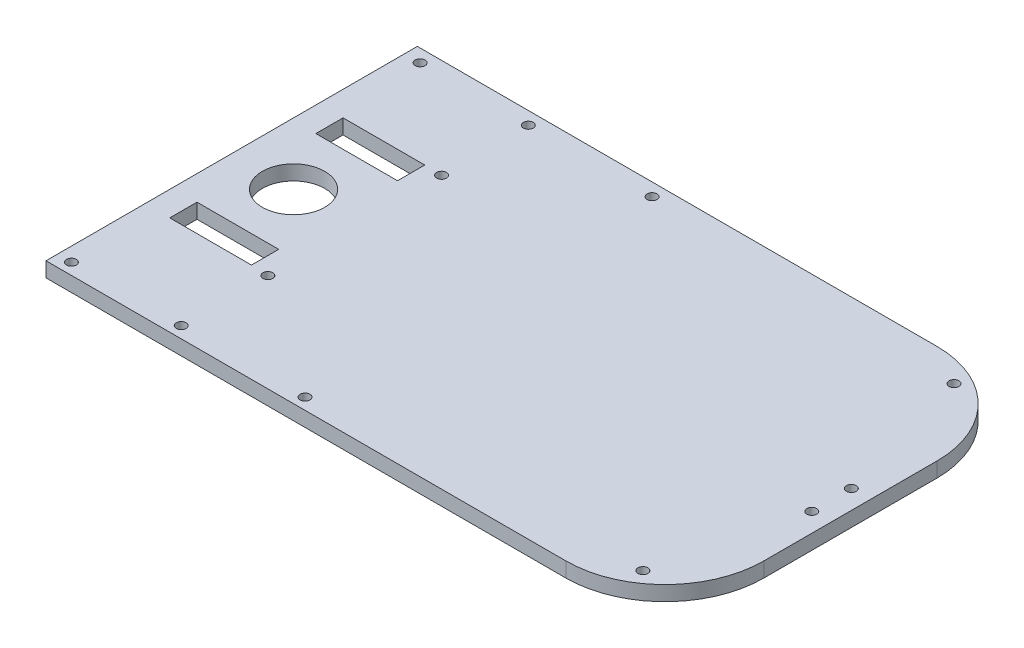
SolidWorks part; units mm, degrees
ref_plane "Front Plane" through (0, 0, 0) normal (0, 0, 1) x (1, 0, 0)
ref_plane "Top Plane" through (0, 0, 0) normal (0, 1, 0) x (1, 0, 0)
ref_plane "Right Plane" through (0, 0, 0) normal (1, 0, 0) x (0, 0, -1)
sketch "Sketch1" plane through (0, 0, 0) normal (0, 1, 0) x (1, 0, 0)
  line L1 (0, 0) -> (210, 0)
  line L2 (0, 0) -> (0, 150)
  line L3 (0, 150) -> (210, 150)
  line L4 (250, 40) -> (250, 110)
  arc A0 (250, 110) -> (210, 150) centre (210, 110) ccw
  arc A1 (210, 0) -> (250, 40) centre (210, 40) ccw
  point P7 (250, 150)
  dimension "D3" = 40
  dimension "D4" = 40
  dimension "D1" = 250
  dimension "D2" = 150
extrude "Boss-Extrude1" add sketch "Sketch1" along normal blind 6
sketch "Sketch2" plane through (0, 0, 0) normal (0, -1, 0) x (1, 0, 0)
  line L0 (0, 0) -> (210, 0) construction
  line L2 (0, -150) -> (0, 0) construction
  circle A0 centre (25, -75) radius 12.5979
  dimension "D1" = 25.1959
  dimension "D2" = 75
  dimension "D3" = 25
extrude "Cut-Extrude1" cut sketch "Sketch2" against normal through all
sketch "Sketch3" plane through (0, 6, 0) normal (0, 1, 0) x (1, 0, 0)
  line L0 (210, 150) -> (0, 150) construction
  line L1 (0, 150) -> (0, 0) construction
  circle A0 centre (6.3109, 144.8171) radius 2
  dimension "D1" = 4
  dimension "D2" = 5.1829
  dimension "D3" = 6.3109
sketch "Sketch4" plane through (0, 6, 0) normal (0, 1, 0) x (1, 0, 0)
  line L0 (0, 0) -> (210, 0) construction
  line L1 (0, 150) -> (0, 0) construction
  circle A0 centre (5.6357, 4.6328) radius 2
  dimension "D1" = 4
  dimension "D2" = 4.6328
  dimension "D3" = 5.6357
sketch "Sketch5" plane through (0, 6, 0) normal (0, 1, 0) x (1, 0, 0)
  circle A0 centre (226.3641, 140.4212) radius 2
  arc A1 (250, 110) -> (210, 150) centre (210, 110) ccw construction
  dimension "D1" = 4
  dimension "D2" = 34.5433
  dimension "D3" = 30.4212
sketch "Sketch6" plane through (0, 6, 0) normal (0, 1, 0) x (1, 0, 0)
  circle A0 centre (228.9499, 12.1646) radius 2
  arc A1 (210, 0) -> (250, 40) centre (210, 40) ccw construction
  dimension "D1" = 4
  dimension "D2" = 33.6736
  dimension "D3" = 18.9499
sketch "Sketch8" plane through (0, 6, 0) normal (0, 1, 0) x (1, 0, 0)
  line L0 (250, 40) -> (250, 110) construction
  line L1 (0, 0) -> (210, 0) construction
  line L2 (210, 150) -> (0, 150) construction
  circle A0 centre (242.3399, 83) radius 2
  circle A1 centre (242.3399, 67) radius 2
  dimension "D1" = 4
  dimension "D3" = 4
  dimension "D4" = 7.6601
  dimension "D2" = 16
  dimension "D5" = 67
  dimension "D6" = 67
sketch "Sketch10" plane through (0, 6, 0) normal (0, 1, 0) x (1, 0, 0)
  line L0 (210, 150) -> (0, 150) construction
  line L1 (0, 150) -> (0, 0) construction
  line L2 (0, 0) -> (210, 0) construction
  circle A0 centre (50, 144.82) radius 2
  circle A1 centre (50, 4.63) radius 2
  circle A3 centre (100, 4.63) radius 2
  circle A4 centre (100, 144.82) radius 2
  circle A5 centre (50, 109.82) radius 2
  circle A6 centre (50, 39.63) radius 2
  dimension "D1" = 4
  dimension "D4" = 4
  dimension "D9" = 4
  dimension "D10" = 4
  dimension "D15" = 4
  dimension "D18" = 4
  dimension "D14" = 50
  dimension "D17" = 50
  dimension "D2" = 5.18
  dimension "D3" = 50
  dimension "D5" = 4.63
  dimension "D6" = 50
  dimension "D7" = 50
  dimension "D8" = 4.63
  dimension "D11" = 50
  dimension "D12" = 5.18
  dimension "D13" = 35
  dimension "D16" = 35
extrude "Cut-Extrude10" cut sketch "Sketch3" against normal through all
extrude "Cut-Extrude11" cut sketch "Sketch4" against normal through all
extrude "Cut-Extrude12" cut sketch "Sketch5" against normal through all
extrude "Cut-Extrude13" cut sketch "Sketch6" against normal through all
extrude "Cut-Extrude14" cut sketch "Sketch8" against normal through all
extrude "Cut-Extrude15" cut sketch "Sketch10" against normal through all
sketch "Sketch13" plane through (0, 6, 0) normal (0, 1, 0) x (1, 0, 0)
  line L0 (0, 150) -> (0, 0) construction
  line L1 (10, 110) -> (43, 110)
  line L2 (10, 110) -> (10, 99)
  line L3 (10, 99) -> (43, 99)
  line L4 (43, 110) -> (43, 99)
  line L15 (10, 51) -> (43, 51)
  line L16 (10, 51) -> (10, 40)
  line L17 (10, 40) -> (43, 40)
  line L18 (43, 51) -> (43, 40)
  circle A0 centre (25, 75) radius 12.5979 construction
  dimension "D1" = 33
  dimension "D2" = 11
  dimension "D3" = 10
  dimension "D4" = 24
  dimension "D5" = 33
  dimension "D6" = 11
  dimension "D7" = 10
  dimension "D14" = 24
extrude "Cut-Extrude16" cut sketch "Sketch13" against normal through all
